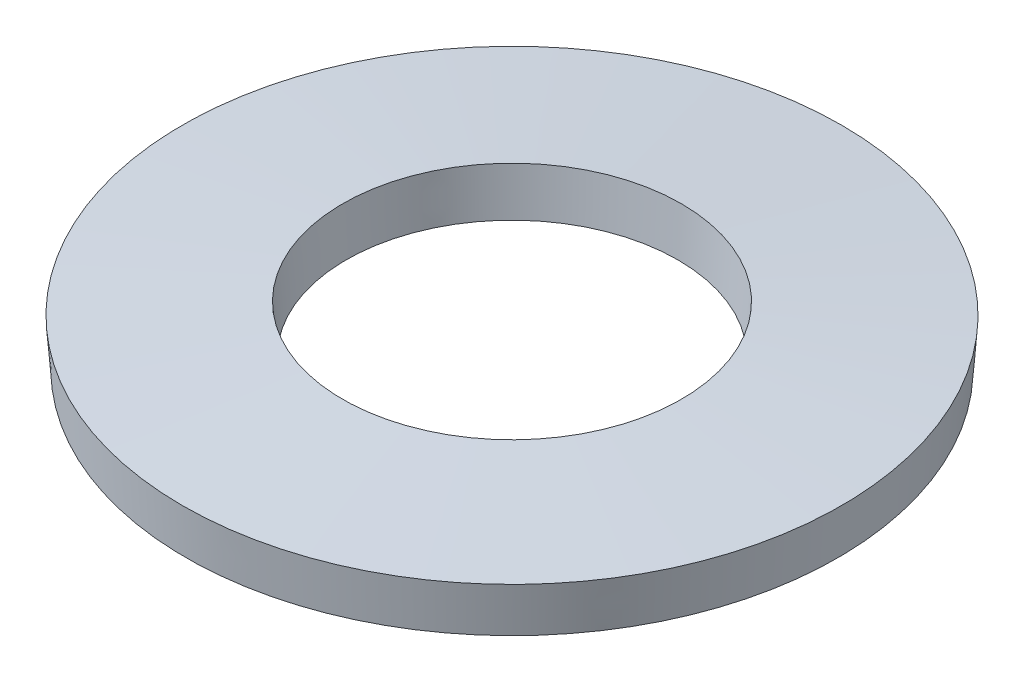
SolidWorks part; units mm, degrees
ref_plane "Front" through (0, 0, 0) normal (0, 0, 1) x (1, 0, 0)
ref_plane "Top" through (0, 0, 0) normal (0, 1, 0) x (1, 0, 0)
ref_plane "Right" through (0, 0, 0) normal (1, 0, 0) x (0, 0, -1)
sketch "Sketch1" plane through (0, 0, 0) normal (0, 0, 1) x (1, 0, 0)
  line L0 (18.847, 0) -> (9.5885, 0.6934)
  line L1 (9.5885, 0.6934) -> (9.7915, 3.4036)
  line L2 (9.7915, 3.4036) -> (19.05, 2.7102)
  line L3 (19.05, 2.7102) -> (18.847, 0)
  line L4 (0, 0) -> (0, 3.4036) construction
  dimension "ID" = 19.177
  dimension "OD" = 38.1
  dimension "Thickness" = 2.7178
  dimension "Height" = 3.4036
revolve "Revolve1" add sketch "Sketch1" angle 360 about L4
